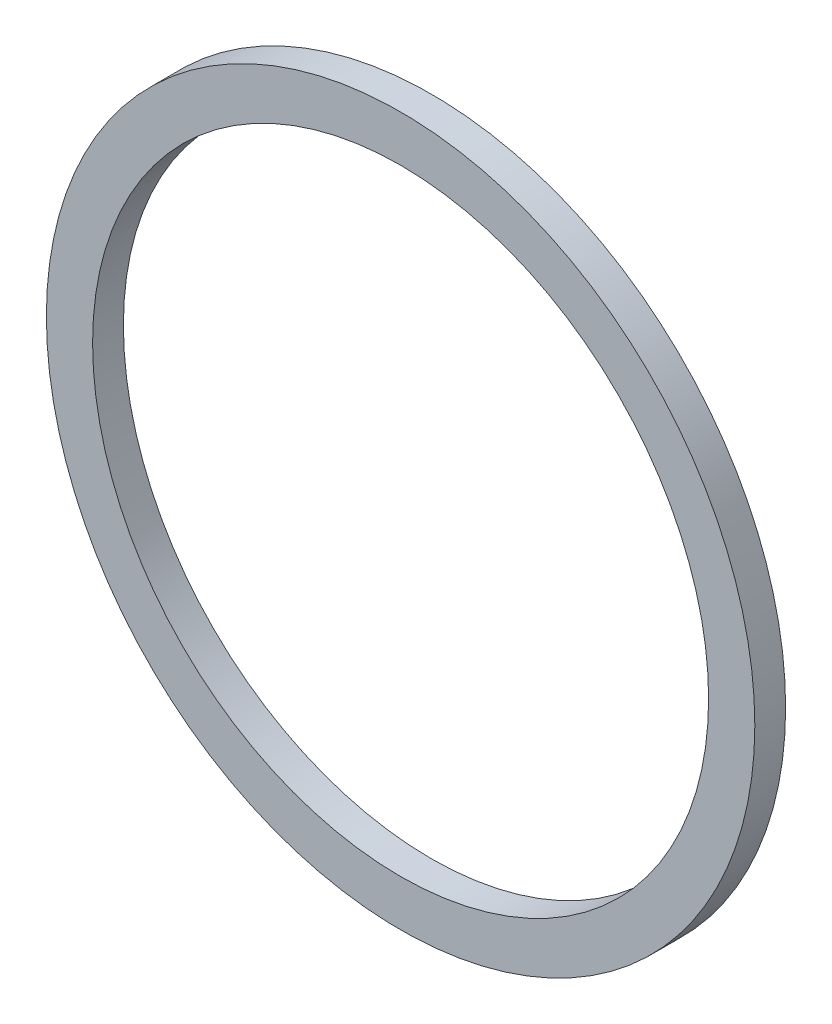
SolidWorks part; units mm, degrees
material "AISI 316 Stainless Steel Sheet (SS)"
ref_plane "Front Plane" through (0, 0, 0) normal (0, 0, 1) x (1, 0, 0)
ref_plane "Top Plane" through (0, 0, 0) normal (0, 1, 0) x (1, 0, 0)
ref_plane "Right Plane" through (0, 0, 0) normal (1, 0, 0) x (0, 0, -1)
sketch "Sketch1" plane through (0, 0, 0) normal (0, 0, 1) x (1, 0, 0)
  circle A0 centre (0, 0) radius 115
  circle A1 centre (0, 0) radius 100
  dimension "D1" = 230
  dimension "D2" = 200
extrude "Boss-Extrude1" add sketch "Sketch1" along normal blind 10
